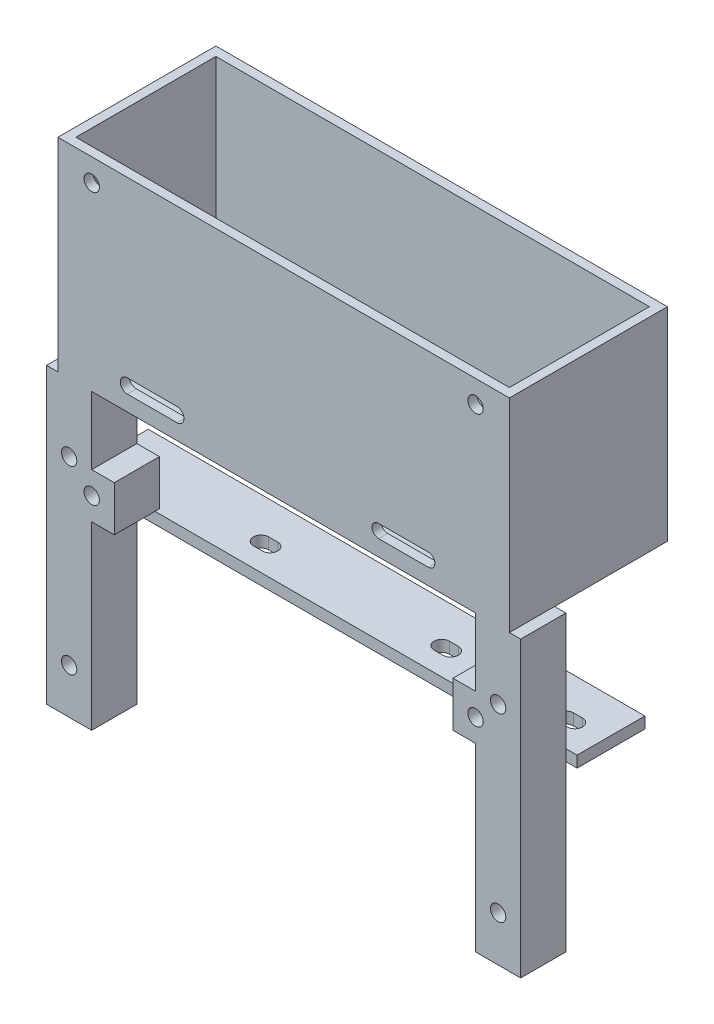
SolidWorks part; units mm, degrees
ref_plane "前视基准面" through (0, 0, 0) normal (0, 0, 1) x (1, 0, 0)
ref_plane "上视基准面" through (0, 0, 0) normal (0, 1, 0) x (1, 0, 0)
ref_plane "右视基准面" through (0, 0, 0) normal (1, 0, 0) x (0, 0, -1)
other "Configuration Table"
sketch "V3 box footprint 100 x 45 mm" plane through (0, 0, 0) normal (0, 0, 1) x (1, 0, 0)
  line L1 (-50, 0) -> (50, 0)
  line L2 (-50, 0) -> (-50, 45)
  line L3 (-50, 45) -> (50, 45)
  line L4 (50, 0) -> (50, 45)
extrude "V3 box height 35 mm" add sketch "V3 box footprint 100 x 45 mm" along normal blind 35
sketch "V3 rear opening 96 x 31 mm" plane through (0, 45, 0) normal (0, 1, 0) x (1, 0, 0)
  line L1 (-48, -2) -> (48, -2)
  line L2 (-48, -2) -> (-48, -33)
  line L3 (-48, -33) -> (48, -33)
  line L4 (48, -2) -> (48, -33)
extrude "V3 cavity all walls 2 mm" cut sketch "V3 rear opening 96 x 31 mm" against normal blind 43
sketch "V3 square beams 10 x 10 pitch 95 mm" plane through (0, 0, 0) normal (0, -1, 0) x (1, 0, 0)
  line L1 (-52.5, 25) -> (-42.5, 25)
  line L2 (-52.5, 25) -> (-52.5, 35)
  line L3 (-52.5, 35) -> (-42.5, 35)
  line L4 (-42.5, 25) -> (-42.5, 35)
  line L6 (42.5, 25) -> (52.5, 25)
  line L7 (42.5, 25) -> (42.5, 35)
  line L8 (42.5, 35) -> (52.5, 35)
  line L9 (52.5, 25) -> (52.5, 35)
extrude "V3 forward beam length 65 mm" add sketch "V3 square beams 10 x 10 pitch 95 mm" along normal blind 65
sketch "V3 left PCB ear profile" plane through (-42.5, 0, 0) normal (1, 0, 0) x (0, 0, -1)
  line L1 (-25, -25) -> (-35, -25)
  line L2 (-25, -25) -> (-25, -15)
  line L3 (-25, -15) -> (-35, -15)
  line L4 (-35, -25) -> (-35, -15)
extrude "V3 left inward ear 5 mm" add sketch "V3 left PCB ear profile" along normal blind 5
sketch "V3 right PCB ear profile" plane through (42.5, 0, 0) normal (-1, 0, 0) x (0, 0, 1)
  line L1 (25, -25) -> (35, -25)
  line L2 (25, -25) -> (25, -15)
  line L3 (25, -15) -> (35, -15)
  line L4 (35, -25) -> (35, -15)
extrude "V3 right inward ear 5 mm" add sketch "V3 right PCB ear profile" along normal blind 5
sketch "V3 PCB roof pair pitch 85 mm" plane through (0, 0, 35) normal (0, 0, 1) x (1, 0, 0)
  circle A0 centre (-42.5, 40) radius 1.7
  circle A1 centre (42.5, 40) radius 1.7
extrude "V3 M3 roof holes diameter 3.4 mm" cut sketch "V3 PCB roof pair pitch 85 mm" against normal blind 2
sketch "V3 PCB forward pair row spacing 60 mm" plane through (0, 0, 35) normal (0, 0, 1) x (1, 0, 0)
  circle A0 centre (-42.5, -20) radius 1.7
  circle A1 centre (42.5, -20) radius 1.7
extrude "V3 M3 PCB ear holes" cut sketch "V3 PCB forward pair row spacing 60 mm" against normal blind 10
sketch "V3 chassis top holes width 95 depth 40 mm" plane through (0, 0, 35) normal (0, 0, 1) x (1, 0, 0)
  circle A0 centre (-47.5, -55) radius 1.7
  circle A1 centre (-47.5, -15) radius 1.7
  circle A2 centre (47.5, -55) radius 1.7
  circle A3 centre (47.5, -15) radius 1.7
extrude "V3 M3 beam top bottom holes" cut sketch "V3 chassis top holes width 95 depth 40 mm" against normal blind 10
sketch "V3 hanging plate offset 26 thickness 2.5 mm" plane through (0, 0, 25) normal (0, 0, -1) x (-1, 0, 0)
  line L1 (55, -28.5) -> (-55, -28.5)
  line L2 (55, -28.5) -> (55, -26)
  line L3 (55, -26) -> (-55, -26)
  line L4 (-55, -28.5) -> (-55, -26)
extrude "V3 mounting plate downward 15 mm width 110" add sketch "V3 hanging plate offset 26 thickness 2.5 mm" along normal blind 15
sketch "V3 slots 6 mm below beam underside centers 20 and 47.5" plane through (0, -28.5, 0) normal (0, -1, 0) x (1, 0, 0)
  line L0 (-48.5, 19) -> (-46.5, 19) construction
  line L1 (-48.5, 20.7) -> (-46.5, 20.7)
  line L2 (-48.5, 17.3) -> (-46.5, 17.3)
  line L3 (-21, 19) -> (-19, 19) construction
  line L4 (-21, 20.7) -> (-19, 20.7)
  line L5 (-21, 17.3) -> (-19, 17.3)
  line L6 (19, 19) -> (21, 19) construction
  line L7 (19, 20.7) -> (21, 20.7)
  line L8 (19, 17.3) -> (21, 17.3)
  line L9 (46.5, 19) -> (48.5, 19) construction
  line L10 (46.5, 20.7) -> (48.5, 20.7)
  line L11 (46.5, 17.3) -> (48.5, 17.3)
  arc A0 (-48.5, 20.7) -> (-48.5, 17.3) centre (-48.5, 19) ccw
  arc A1 (-46.5, 17.3) -> (-46.5, 20.7) centre (-46.5, 19) ccw
  arc A2 (-21, 20.7) -> (-21, 17.3) centre (-21, 19) ccw
  arc A3 (-19, 17.3) -> (-19, 20.7) centre (-19, 19) ccw
  arc A4 (19, 20.7) -> (19, 17.3) centre (19, 19) ccw
  arc A5 (21, 17.3) -> (21, 20.7) centre (21, 19) ccw
  arc A6 (46.5, 20.7) -> (46.5, 17.3) centre (46.5, 19) ccw
  arc A7 (48.5, 17.3) -> (48.5, 20.7) centre (48.5, 19) ccw
  point P2 (-47.5, 19)
  point P7 (-20, 19)
  point P14 (20, 19)
  point P21 (47.5, 19)
  dimension "D1" = 3.4
  dimension "D2" = 2
  dimension "D3" = 3.4
  dimension "D4" = 2
  dimension "D5" = 3.4
  dimension "D6" = 2
  dimension "D7" = 3.4
  dimension "D8" = 2
extrude "Four horizontal slots 3.4 x 5.4 mm" cut sketch "V3 slots 6 mm below beam underside centers 20 and 47.5" against normal blind 2.5
sketch "草图1" plane through (0, 0, 35) normal (0, 0, 1) x (1, 0, 0)
  line L0 (-34.6201, 5) -> (-23.6201, 5) construction
  line L1 (-34.6201, 6.488) -> (-23.6201, 6.488)
  line L2 (-34.6201, 3.512) -> (-23.6201, 3.512)
  line L3 (21.03, 5) -> (32.03, 5) construction
  line L6 (21.03, 6.488) -> (32.03, 6.488)
  line L7 (21.03, 3.512) -> (32.03, 3.512)
  arc A0 (-34.6201, 6.488) -> (-34.6201, 3.512) centre (-34.6201, 5) ccw
  arc A1 (-23.6201, 3.512) -> (-23.6201, 6.488) centre (-23.6201, 5) ccw
  arc A4 (21.03, 6.488) -> (21.03, 3.512) centre (21.03, 5) ccw
  arc A5 (32.03, 3.512) -> (32.03, 6.488) centre (32.03, 5) ccw
  point P2 (-29.1201, 5)
  point P9 (26.53, 5)
sketch "草图2" plane through (0, 0, 0) normal (0, 0, -1) x (-1, 0, 0)
  line L0 (-32.03, 5) -> (-21.03, 5) construction
  line L1 (-32.03, 6.4595) -> (-21.03, 6.4595)
  line L2 (-32.03, 3.5405) -> (-21.03, 3.5405)
  line L3 (23.6201, 5) -> (34.6201, 5) construction
  line L4 (23.6201, 6.5587) -> (34.6201, 6.5587)
  line L5 (23.6201, 3.4413) -> (34.6201, 3.4413)
  arc A0 (-32.03, 6.4595) -> (-32.03, 3.5405) centre (-32.03, 5) ccw
  arc A1 (-21.03, 3.5405) -> (-21.03, 6.4595) centre (-21.03, 5) ccw
  arc A2 (23.6201, 6.5587) -> (23.6201, 3.4413) centre (23.6201, 5) ccw
  arc A3 (34.6201, 3.4413) -> (34.6201, 6.5587) centre (34.6201, 5) ccw
  point P4 (-26.53, 5)
  point P9 (29.1201, 5)
extrude "切除-拉伸1" cut sketch "草图2" against normal through all
